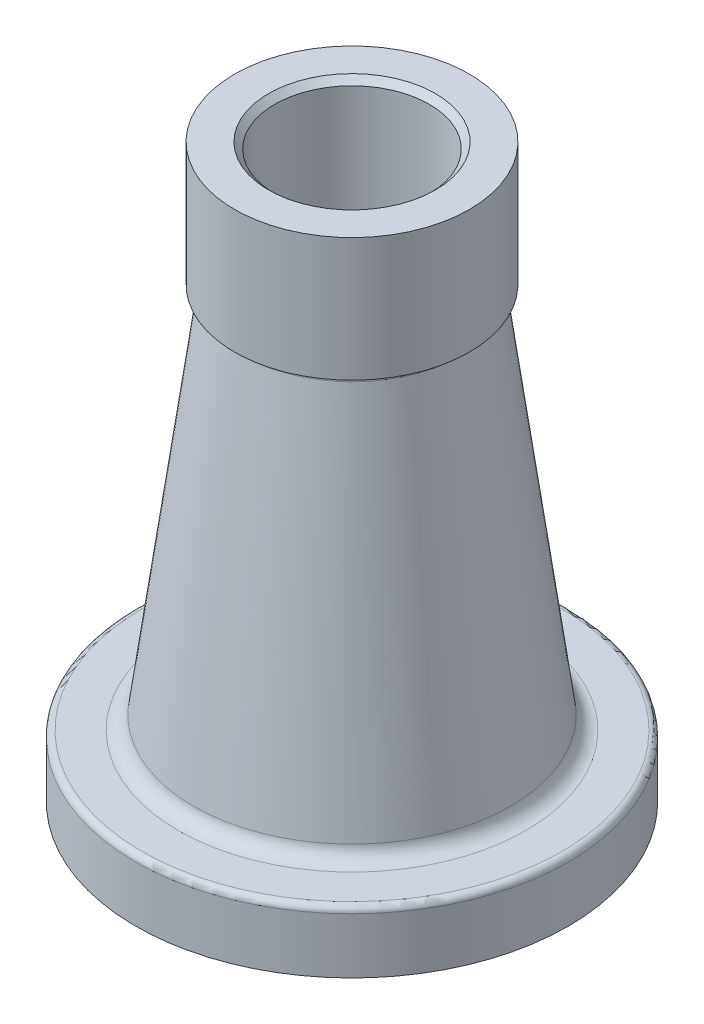
SolidWorks part; units mm, degrees
ref_plane "Front Plane" through (0, 0, 0) normal (0, 0, 1) x (1, 0, 0)
ref_plane "Top Plane" through (0, 0, 0) normal (0, 1, 0) x (1, 0, 0)
ref_plane "Right Plane" through (0, 0, 0) normal (1, 0, 0) x (0, 0, -1)
sketch "Sketch1" plane through (0, 0, 0) normal (0, 0, 1) x (1, 0, 0)
  line L0 (0, -92.5) -> (0, 92.5)
  line L1 (0, 92.5) -> (38, 92.5)
  line L2 (0, -92.5) -> (50, -92.5)
  line L3 (0, -92.5) -> (0, -88.6573)
  line L4 (0, -88.6573) -> (50, -88.6573)
  line L5 (50, -92.5) -> (50, -88.6573)
  line L6 (38, 92.5) -> (38, 52.5)
  line L7 (44, -88.6573) -> (25.0398, 52.5)
  line L9 (0, -92.5) -> (70, -92.5)
  line L10 (70, -92.5) -> (70, -72.5)
  line L11 (70, -72.5) -> (51.9196, -72.5)
  line L12 (51.9196, -72.5) -> (35.1296, 52.5)
  line L13 (35.1296, 52.5) -> (38, 52.5)
  line L14 (25.0398, 52.5) -> (25.0398, 92.5)
  line L15 (0, 92.5) -> (25.0398, 92.5)
  line L16 (0, 92.5) -> (0, 90.5)
  line L17 (0, 90.5) -> (25.0398, 90.5)
  line L18 (25.0398, 92.5) -> (25.0398, 90.5)
  point P4 (0, 0)
  dimension "D1" = 44
  dimension "D2" = 50
  dimension "D3" = 38
  dimension "D4" = 40
  dimension "D5" = 185
  dimension "D6" = 10
  dimension "D8" = 20
revolve "Revolve1" add sketch "Sketch1" angle 360 about L0
fillet "Fillet1" radius 5 1 edges at (51.9196, -72.5, 0)
chamfer "Chamfer1" distance 2 angle 45 1 edges at (25.0398, 92.5, 0)
fillet "Fillet2" radius 1 1 edges at (50, -88.6573, 0)
fillet "Fillet3" radius 2 1 edges at (70, -72.5, 0)
fillet "Fillet4" radius 2 1 edges at (35.1296, 52.5, 0)
